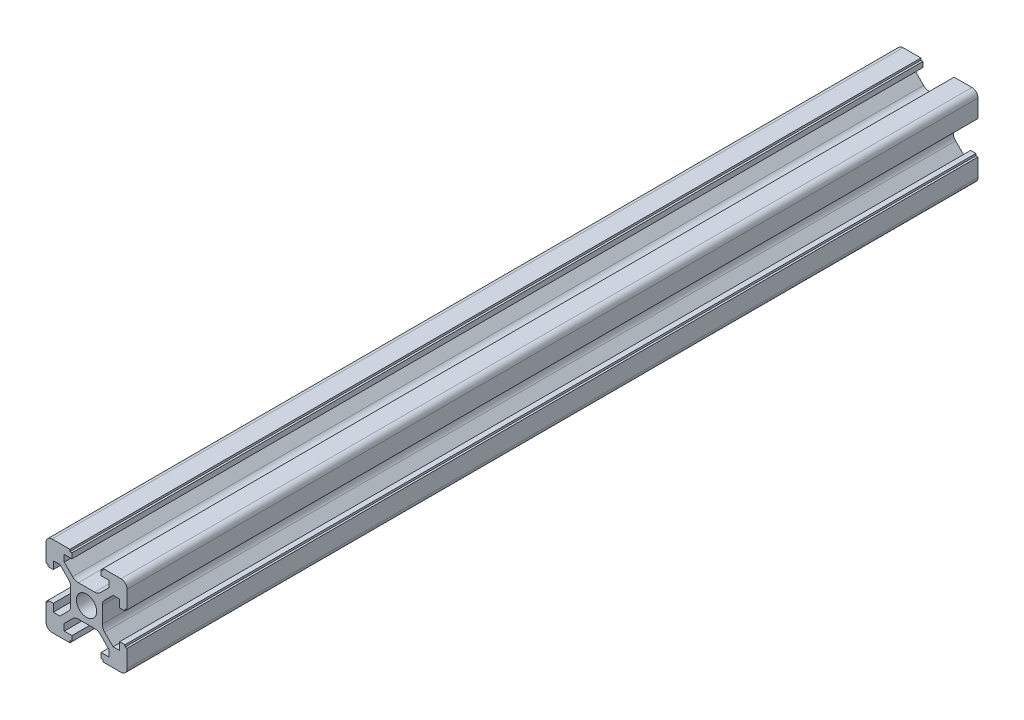
SolidWorks part; units mm, degrees
ref_plane "Front Plane" through (0, 0, 0) normal (0, 0, 1) x (1, 0, 0)
ref_plane "Top Plane" through (0, 0, 0) normal (0, 1, 0) x (1, 0, 0)
ref_plane "Right Plane" through (0, 0, 0) normal (1, 0, 0) x (0, 0, -1)
sketch "Sketch1" plane through (0, 0, 0) normal (0, 0, 1) x (1, 0, 0)
  line L0 (10, -4.1) -> (10, -8.5)
  line L1 (4.1, 10) -> (8.5, 10)
  line L2 (8.5, -10) -> (4.1, -10)
  line L3 (-8.5, -10) -> (-4.1, -10)
  line L4 (10, 8.5) -> (10, 4.1)
  line L7 (8.5, 10) -> (4.1, 10)
  line L8 (5.5, 6.5607) -> (3.4251, 4.4858)
  line L9 (8.5, 10) -> (4.1, 10)
  line L10 (3.9, 2.0109) -> (3.9, -2.0109)
  line L11 (2.0109, -3.9) -> (-2.0109, -3.9)
  line L12 (-3.9, -2.0109) -> (-3.9, 2.0109)
  line L13 (-2.0109, 3.9) -> (2.8393, 3.9)
  line L14 (2.5, 0) -> (22.2403, 0) construction
  line L15 (3.6, 9.5) -> (3.6, 8.2)
  line L16 (9.5, 3.6) -> (8.2, 3.6)
  line L17 (8.2, 3.6) -> (8.2, 5.5)
  line L18 (8.2, 5.5) -> (6.5607, 5.5)
  line L19 (10, -4.1) -> (10, -8.5)
  line L20 (4.1, 9.5) -> (3.6, 9.5)
  line L21 (4.1, 10) -> (4.1, 9.5)
  line L22 (8.5, 10) -> (4.1, 10)
  line L23 (10, 4.1) -> (9.5, 4.1)
  line L24 (9.5, 4.1) -> (9.5, 3.6)
  line L25 (5.5, 8.2) -> (5.5, 6.5607)
  line L26 (3.6, 8.2) -> (5.5, 8.2)
  line L27 (4.4858, 3.4251) -> (6.5607, 5.5)
  line L28 (10, -8.5) -> (10, -4.1)
  line L29 (6.5607, -5.5) -> (4.4858, -3.4251)
  line L30 (10, -8.5) -> (10, -4.1)
  line L31 (2.0109, -3.9) -> (-2.0109, -3.9)
  line L32 (3.9, 2.8393) -> (3.9, -2.0109)
  line L33 (9.5, -3.6) -> (8.2, -3.6)
  line L34 (3.6, -9.5) -> (3.6, -8.2)
  line L35 (3.6, -8.2) -> (5.5, -8.2)
  line L36 (5.5, -8.2) -> (5.5, -6.5607)
  line L37 (9.5, -4.1) -> (9.5, -3.6)
  line L38 (10, -4.1) -> (9.5, -4.1)
  line L39 (10, -8.5) -> (10, -4.1)
  line L40 (4.1, -10) -> (4.1, -9.5)
  line L41 (4.1, -9.5) -> (3.6, -9.5)
  line L42 (8.2, -5.5) -> (6.5607, -5.5)
  line L43 (8.2, -3.6) -> (8.2, -5.5)
  line L44 (3.4251, -4.4858) -> (5.5, -6.5607)
  line L45 (-4.1, -10) -> (-8.5, -10)
  line L46 (-10, -8.5) -> (-10, -4.1)
  line L47 (-8.5, -10) -> (-4.1, -10)
  line L48 (-5.5, -6.5607) -> (-3.4251, -4.4858)
  line L49 (-8.5, -10) -> (-4.1, -10)
  line L50 (-3.9, -2.0109) -> (-3.9, 2.0109)
  line L51 (2.0109, -3.9) -> (-2.0109, -3.9)
  line L52 (-3.6, -9.5) -> (-3.6, -8.2)
  line L53 (-9.5, -3.6) -> (-8.2, -3.6)
  line L54 (-8.2, -3.6) -> (-8.2, -5.5)
  line L55 (-8.2, -5.5) -> (-6.5607, -5.5)
  line L56 (-4.1, -9.5) -> (-3.6, -9.5)
  line L57 (-4.1, -10) -> (-4.1, -9.5)
  line L58 (-8.5, -10) -> (-4.1, -10)
  line L59 (-10, -4.1) -> (-9.5, -4.1)
  line L60 (-9.5, -4.1) -> (-9.5, -3.6)
  line L61 (-5.5, -8.2) -> (-5.5, -6.5607)
  line L62 (-3.6, -8.2) -> (-5.5, -8.2)
  line L63 (-4.4858, -3.4251) -> (-6.5607, -5.5)
  line L64 (-10, 4.1) -> (-10, 8.5)
  line L65 (-8.5, 10) -> (-4.1, 10)
  line L66 (-10, 8.5) -> (-10, 4.1)
  line L67 (-6.5607, 5.5) -> (-4.4858, 3.4251)
  line L68 (-10, 8.5) -> (-10, 4.1)
  line L69 (-2.0109, 3.9) -> (2.0109, 3.9)
  line L70 (-3.9, -2.0109) -> (-3.9, 2.0109)
  line L71 (-9.5, 3.6) -> (-8.2, 3.6)
  line L72 (-3.6, 9.5) -> (-3.6, 8.2)
  line L73 (-3.6, 8.2) -> (-5.5, 8.2)
  line L74 (-5.5, 8.2) -> (-5.5, 6.5607)
  line L75 (-9.5, 4.1) -> (-9.5, 3.6)
  line L76 (-10, 4.1) -> (-9.5, 4.1)
  line L77 (-10, 8.5) -> (-10, 4.1)
  line L78 (-4.1, 10) -> (-4.1, 9.5)
  line L79 (-4.1, 9.5) -> (-3.6, 9.5)
  line L80 (-8.2, 5.5) -> (-6.5607, 5.5)
  line L81 (-8.2, 3.6) -> (-8.2, 5.5)
  line L82 (-3.4251, 4.4858) -> (-5.5, 6.5607)
  line L83 (4.1, -10) -> (8.5, -10)
  arc A0 (2.0109, -3.9) -> (3.4251, -4.4858) centre (2.0109, -5.9) cw
  arc A1 (4.4858, -3.4251) -> (3.9, -2.0109) centre (5.9, -2.0109) cw
  arc A2 (3.9, 2.0109) -> (4.4858, 3.4251) centre (5.9, 2.0109) cw
  arc A3 (2.0109, 3.9) -> (3.4251, 4.4858) centre (2.0109, 5.9) ccw
  arc A4 (-2.0109, 3.9) -> (-3.4251, 4.4858) centre (-2.0109, 5.9) cw
  arc A5 (-4.4858, 3.4251) -> (-3.9, 2.0109) centre (-5.9, 2.0109) cw
  arc A6 (-3.4251, -4.4858) -> (-2.0109, -3.9) centre (-2.0109, -5.9) cw
  arc A7 (-3.9, -2.0109) -> (-4.4858, -3.4251) centre (-5.9, -2.0109) cw
  circle A8 centre (0, 0) radius 2.5
  arc A9 (-8.5, -10) -> (-10, -8.5) centre (-8.5, -8.5) cw
  arc A10 (-10, 8.5) -> (-8.5, 10) centre (-8.5, 8.5) cw
  arc A11 (8.5, 10) -> (10, 8.5) centre (8.5, 8.5) cw
  arc A12 (8.5, -10) -> (10, -8.5) centre (8.5, -8.5) ccw
  point P0 (0, 0)
  point P86 (0, 0)
  point P107 (10, -10)
  dimension "D3" = 2
  dimension "D5" = 5
  dimension "D2" = 1.5
  dimension "D8" = 1.5
  dimension "D4" = 6.1
  dimension "D6" = 20
  dimension "D7" = 6.1
  dimension "D9" = 20
  dimension "D11" = 0.5
  dimension "D12" = 0.5
extrude "Boss-Extrude2" add sketch "Sketch1" along normal blind 210
